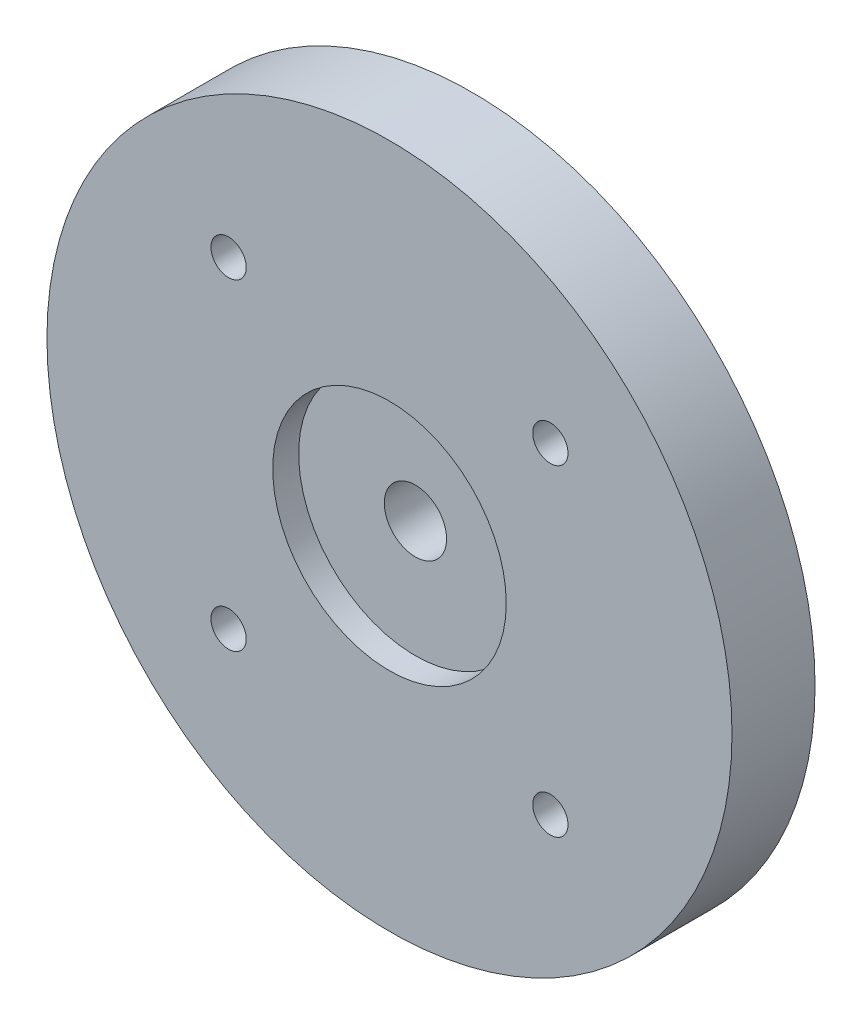
SolidWorks part; units mm, degrees
ref_plane "Front Plane" through (0, 0, 0) normal (0, 0, 1) x (1, 0, 0)
ref_plane "Top Plane" through (0, 0, 0) normal (0, 1, 0) x (1, 0, 0)
ref_plane "Right Plane" through (0, 0, 0) normal (1, 0, 0) x (0, 0, -1)
sketch "Sketch2" plane through (0, 0, 0) normal (0, 0, 1) x (1, 0, 0)
  circle A0 centre (0, 0) radius 33
  dimension "D1" = 66
extrude "Boss-Extrude1" add sketch "Sketch2" along normal blind 8
sketch "Sketch6" plane through (0, 0, 0) normal (0, 0, -1) x (-1, 0, 0)
  circle A0 centre (0, 0) radius 10
  dimension "D1" = 20
extrude "Boss-Extrude2" add sketch "Sketch6" along normal blind 2
sketch "Sketch3" plane through (0, 0, 8) normal (0, 0, 1) x (1, 0, 0)
  line L0 (0, -15.5) -> (0, 15.5) construction
  line L1 (15.5, 15.5) -> (-15.5, 15.5) construction
  line L2 (15.5, -15.5) -> (-15.5, -15.5) construction
  circle A0 centre (-15.5, 15.5) radius 1.7
  circle A1 centre (15.5, 15.5) radius 1.7
  circle A2 centre (15.5, -15.5) radius 1.7
  circle A3 centre (-15.5, -15.5) radius 1.7
  circle A4 centre (0, 0) radius 3
  point P12 (0, 0)
  point P16 (0, 15.5)
  point P19 (0, -15.5)
  dimension "D1" = 3.4
  dimension "D2" = 3.4
  dimension "D3" = 3.4
  dimension "D4" = 3.4
  dimension "D8" = 6
  dimension "D5" = 31
  dimension "D6" = 31
  dimension "D7" = 31
extrude "Cut-Extrude1" cut sketch "Sketch3" against normal through all both and the other way through all
sketch "Sketch4" plane through (0, 0, 0) normal (0, 0, -1) x (-1, 0, 0)
  circle A0 centre (-15.5, 15.5) radius 2.8
  circle A1 centre (15.5, 15.5) radius 2.8
  circle A2 centre (15.5, -15.5) radius 2.8
  circle A3 centre (-15.5, -15.5) radius 2.8
  dimension "D1" = 5.6
  dimension "D2" = 5.6
  dimension "D3" = 5.6
  dimension "D4" = 5.6
extrude "Cut-Extrude2" cut sketch "Sketch4" against normal blind 2 and the other way through all
sketch "Sketch5" plane through (0, 0, 0) normal (0, 0, -1) x (-1, 0, 0)
  circle A0 centre (0, 29.5) radius 2.1
  circle A1 centre (29.5, 0) radius 2.1
  circle A2 centre (0, -29.5) radius 2.1
  circle A3 centre (-29.5, 0) radius 2.1
  point P19 (0, 0)
  dimension "D1" = 4.2
  dimension "D2" = 29.5
  dimension "D3" = 4
extrude "Cut-Extrude3" cut sketch "Sketch5" against normal blind 6
fillet "Fillet1" radius 1 1 edges at (-10, 0, 0)
sketch "Sketch7" plane through (0, 0, 8) normal (0, 0, 1) x (1, 0, 0)
  circle A0 centre (0, 0) radius 11.25
  dimension "D1" = 22.5
extrude "Cut-Extrude4" cut sketch "Sketch7" against normal blind 2.5
equation "\"N_pins\"= 26"
equation "\"N_lobes\"= \"N_pins\" - 1"
equation "\"R_pc\"= 25"
equation "\"D_pin\"= 3"
equation "\"R_pin\"= \"D_pin\" / 2"
equation "\"ecc\"= 0.72"
equation "\"t_disc\"= 7"
equation "\"N_out\"= 8"
equation "\"D_outc\"=22"
equation "\"D_roller\"= 5"
equation "\"D_outhole\"= \"D_roller\" + 2 * \"ecc\""
equation "\"D_cam_OD\"= 21"
equation "\"D_cam_ID\"= 10"
equation "\"clr_bore\"= 1"
equation "\"D_bore\"= 2 * \"R_pc\" + \"clr_bore\""
equation "\"t_wall\"= 7.5"
equation "\"D_housing\"= \"D_bore\" + 2 * \"t_wall\""
equation "\"D1@Sketch2\"=\"D_housing\""
